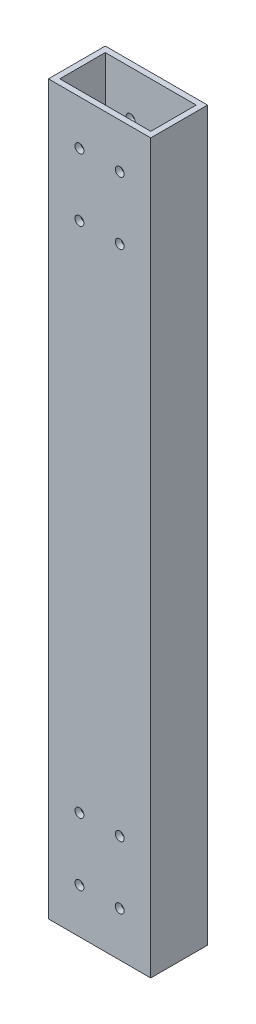
SolidWorks part; units mm, degrees
material "Thornel VCB-20 Carbon Cloth"
ref_plane "Front Plane" through (0, 0, 0) normal (0, 0, 1) x (1, 0, 0)
ref_plane "Top Plane" through (0, 0, 0) normal (0, 1, 0) x (1, 0, 0)
ref_plane "Right Plane" through (0, 0, 0) normal (1, 0, 0) x (0, 0, -1)
sketch "Sketch1" plane through (0, 0, 0) normal (0, 1, 0) x (1, 0, 0)
  line L0 (-25.4, 0) -> (-28.575, 0) construction
  line L1 (-25.4, -12.7) -> (25.4, -12.7)
  line L2 (-25.4, -12.7) -> (-25.4, 12.7)
  line L3 (-25.4, 12.7) -> (25.4, 12.7)
  line L4 (25.4, -12.7) -> (25.4, 12.7)
  line L5 (-25.4, -12.7) -> (25.4, 12.7) construction
  line L6 (-25.4, 12.7) -> (25.4, -12.7) construction
  line L7 (-28.575, -15.875) -> (28.575, -15.875)
  line L8 (-28.575, -15.875) -> (-28.575, 15.875)
  line L9 (-28.575, 15.875) -> (28.575, 15.875)
  line L10 (28.575, -15.875) -> (28.575, 15.875)
  line L11 (-28.575, -15.875) -> (28.575, 15.875) construction
  line L12 (-28.575, 15.875) -> (28.575, -15.875) construction
  line L13 (0, -12.7) -> (0, -15.875) construction
  point P0 (0, 0)
  point P6 (0, 0)
  dimension "D3" = 3.175
  dimension "D1" = 25.4
  dimension "D2" = 50.8
extrude "Boss-Extrude1" add sketch "Sketch1" along normal blind 406.4
sketch "Sketch2" plane through (0, 0, 15.875) normal (0, 0, 1) x (1, 0, 0)
  line L1 (-11.25, 25) -> (11.25, 25) construction
  line L2 (-11.25, 25) -> (-11.25, 60) construction
  line L3 (-11.25, 60) -> (11.25, 60) construction
  line L4 (11.25, 25) -> (11.25, 60) construction
  circle A0 centre (-11.25, 60) radius 2.5
  circle A1 centre (-11.25, 25) radius 2.5
  circle A2 centre (11.25, 25) radius 2.5
  circle A3 centre (11.25, 60) radius 2.5
  point P4 (0, 25)
  dimension "D4" = 5
  dimension "D1" = 22.5
  dimension "D2" = 35
  dimension "D3" = 25
extrude "Cut-Extrude1" cut sketch "Sketch2" against normal through all
ref_plane "Plane1" through (0, 203.2, 0) normal (0, -1, 0) x (-1, 0, 0)
mirror "Mirror1" about plane through (0, 203.2, 0) normal (0, -1, 0) of "Cut-Extrude1"
equation "\"tube_width\"= 1in"
equation "\"tube_height\"= 2in"
equation "\"tube_thickness\"= 0.125in"
equation "\"D3@Sketch1\"=\"tube_thickness\""
equation "\"tube_length\"= 1.5ft"
equation "\"D1@Boss-Extrude1\"=\"tube_length\""
equation "\"D1@Sketch1\"=\"tube_width\""
equation "\"D2@Sketch1\"=\"tube_height\""
